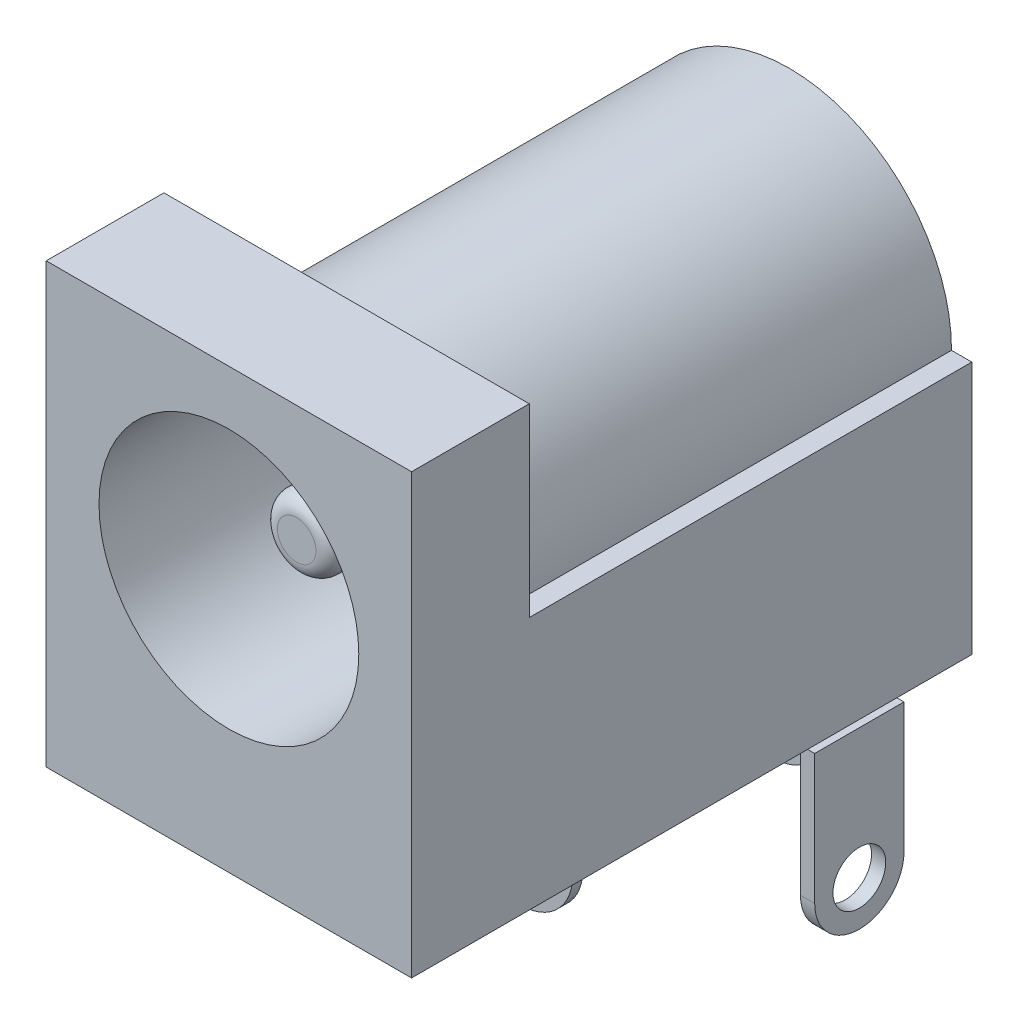
SolidWorks part; units mm, degrees
ref_plane "Front Plane" through (0, 0, 0) normal (0, 0, 1) x (1, 0, 0)
ref_plane "Top Plane" through (0, 0, 0) normal (0, 1, 0) x (1, 0, 0)
ref_plane "Right Plane" through (0, 0, 0) normal (1, 0, 0) x (0, 0, -1)
sketch "Sketch1" plane through (0, 0, 0) normal (0, 0, 1) x (1, 0, 0)
  line L1 (0, 0) -> (9, 0)
  line L2 (0, 0) -> (0, 10.8)
  line L3 (0, 10.8) -> (9, 10.8)
  line L4 (9, 0) -> (9, 10.8)
  dimension "D1" = 10.8
  dimension "D2" = 9
extrude "Boss-Extrude1" add sketch "Sketch1" along normal blind 2.9
sketch "Sketch2" plane through (0, 0, 0) normal (0, 0, -1) x (-1, 0, 0)
  line L0 (0, 10.8) -> (0, 0) construction
  line L1 (-9, 0) -> (0, 0)
  line L2 (-9, 0) -> (-9, 6.24)
  line L3 (-9, 6.24) -> (-8.4999, 6.24)
  line L4 (0, 0) -> (0, 6.24)
  line L5 (-4.5, 0) -> (-4.5, 10.8) construction
  line L6 (-9, 10.8) -> (0, 10.8) construction
  line L7 (-0.5001, 6.24) -> (0, 6.24)
  circle A0 centre (-4.5, 6.26) radius 3.22 construction
  arc A1 (-0.5001, 6.24) -> (-8.4999, 6.24) centre (-4.5, 6.26) ccw
  point P11 (-4.5, 10.26)
  point P14 (-4.5, 3.04)
  point P16 (-4.5, 6.26)
  dimension "D3" = 6.44
  dimension "D5" = 8
  dimension "D1" = 6.24
  dimension "D2" = 10.26
  dimension "D4" = 3.04
  dimension "D6" = 6.26
extrude "Boss-Extrude2" add sketch "Sketch2" along normal blind 10.9
sketch "Sketch3" plane through (0, 0, 2.9) normal (0, 0, 1) x (1, 0, 0)
  line L0 (4.5, 10.8) -> (4.5, 0) construction
  line L1 (9, 10.8) -> (0, 10.8) construction
  line L2 (0, 0) -> (9, 0) construction
  circle A0 centre (4.5, 6.26) radius 3.2
  dimension "D2" = 6.4
  dimension "D1" = 6.26
extrude "Cut-Extrude1" cut sketch "Sketch3" against normal blind 9.54
sketch "Sketch4" plane through (0, 0, -6.64) normal (0, 0, 1) x (1, 0, 0)
  circle A0 centre (4.5, 6.26) radius 0.875
  dimension "D1" = 1.75
extrude "Boss-Extrude3" add sketch "Sketch4" along normal offset from surface (7.87 mm away) 1.67 up to face at (7.7, 6.26, 2.9)
fillet "Fillet1" radius 0.4 1 edges at (3.625, 6.26, 1.23)
sketch "Sketch5" plane through (0, 0, 0) normal (0, -1, 0) x (1, 0, 0)
  line L0 (4.5, 2.9) -> (4.5, -10.9) construction
  line L1 (0, 2.9) -> (9, 2.9) construction
  line L2 (9, -10.9) -> (0, -10.9) construction
  line L3 (9, 2.9) -> (9, -10.9) construction
  line L4 (3.23, -4.55) -> (5.77, -4.55)
  line L5 (3.23, -4.55) -> (3.23, -4.3)
  line L6 (3.23, -4.3) -> (5.77, -4.3)
  line L7 (5.77, -4.55) -> (5.77, -4.3)
  line L8 (3.23, -4.55) -> (5.77, -4.3) construction
  line L9 (3.23, -4.3) -> (5.77, -4.55) construction
  line L10 (3.35, -10.905) -> (5.65, -10.905)
  line L11 (3.35, -10.905) -> (3.35, -10.555)
  line L12 (3.35, -10.555) -> (5.65, -10.555)
  line L13 (5.65, -10.905) -> (5.65, -10.555)
  line L14 (3.35, -10.905) -> (5.65, -10.555) construction
  line L15 (3.35, -10.555) -> (5.65, -10.905) construction
  line L16 (8.825, -9.055) -> (9.175, -9.055)
  line L17 (8.825, -9.055) -> (8.825, -6.855)
  line L18 (8.825, -6.855) -> (9.175, -6.855)
  line L19 (9.175, -9.055) -> (9.175, -6.855)
  line L20 (8.825, -9.055) -> (9.175, -6.855) construction
  line L21 (8.825, -6.855) -> (9.175, -9.055) construction
  point P6 (4.5, -4.425)
  point P11 (4.5, -10.73)
  point P16 (9, -7.955)
  dimension "D1" = 0.25
  dimension "D2" = 2.54
  dimension "D3" = 7.2
  dimension "D4" = 0.35
  dimension "D5" = 2.3
  dimension "D6" = 2.2
  dimension "D7" = 0.35
  dimension "D8" = 2.6
  dimension "D9" = 6.305
  dimension "D10" = 0.17
extrude "Boss-Extrude4" add sketch "Sketch5" along normal blind 4.3
sketch "Sketch6" plane through (0, 0, -4.3) normal (0, 0, 1) x (1, 0, 0)
  line L0 (4.5, -4.3) -> (4.5, -3.03) construction
  line L1 (5.77, -4.3) -> (3.23, -4.3) construction
  line L12 (3.23, -3.03) -> (2.9815, -3.03)
  line L13 (2.9815, -3.03) -> (2.9815, -4.4816)
  line L14 (2.9815, -4.4816) -> (5.9316, -4.4816)
  line L15 (5.9316, -4.4816) -> (5.9316, -3.03)
  line L16 (5.9316, -3.03) -> (5.77, -3.03)
  circle A3 centre (4.5, -3.03) radius 0.65
  arc A5 (3.23, -3.03) -> (5.77, -3.03) centre (4.5, -3.03) ccw
  dimension "D2" = 1.3
  dimension "D1" = 1.27
extrude "Cut-Extrude2" cut sketch "Sketch6" against normal up to next
sketch "Sketch7" plane through (9.175, 0, 0) normal (1, 0, 0) x (0, 0, -1)
  line L0 (7.955, -4.3) -> (7.955, -3.2) construction
  line L1 (9.055, -4.3) -> (6.855, -4.3) construction
  line L14 (6.855, -3.2) -> (6.5371, -3.2)
  line L15 (6.5371, -3.2) -> (6.5371, -4.5568)
  line L16 (6.5371, -4.5568) -> (9.4158, -4.5568)
  line L17 (9.4158, -4.5568) -> (9.4158, -3.2)
  line L18 (9.4158, -3.2) -> (9.055, -3.2)
  circle A3 centre (7.955, -3.2) radius 0.65
  arc A5 (6.855, -3.2) -> (9.055, -3.2) centre (7.955, -3.2) ccw
  dimension "D2" = 1.3
  dimension "D1" = 1.1
extrude "Cut-Extrude3" cut sketch "Sketch7" against normal through all
sketch "Sketch9" plane through (0, 0, -10.905) normal (0, 0, -1) x (-1, 0, 0)
  line L0 (-3.35, -4.3) -> (-5.65, -4.3) construction
  line L1 (-4.5, -4.3) -> (-4.5, -3.15) construction
  line L2 (-5.65, -3.15) -> (-6.0634, -3.15)
  line L3 (-6.0634, -3.15) -> (-6.0634, -4.563)
  line L4 (-6.0634, -4.563) -> (-3.002, -4.563)
  line L5 (-3.002, -4.563) -> (-3.002, -3.15)
  line L6 (-3.002, -3.15) -> (-3.35, -3.15)
  circle A0 centre (-4.5, -3.15) radius 0.65
  arc A1 (-5.65, -3.15) -> (-3.35, -3.15) centre (-4.5, -3.15) ccw
  dimension "D2" = 1.3
  dimension "D1" = 1.15
extrude "Cut-Extrude5" cut sketch "Sketch9" against normal up to next
